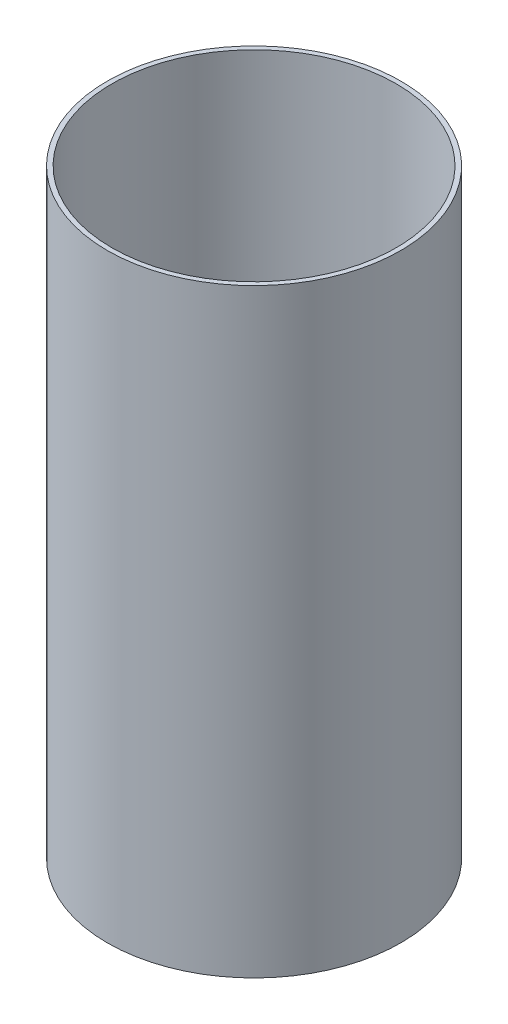
SolidWorks part; units mm, degrees
material "6061-T6 (SS)"
ref_plane "Front Plane" through (0, 0, 0) normal (0, 0, 1) x (1, 0, 0)
ref_plane "Top Plane" through (0, 0, 0) normal (0, 1, 0) x (1, 0, 0)
ref_plane "Right Plane" through (0, 0, 0) normal (1, 0, 0) x (0, 0, -1)
sketch "Sketch1" plane through (0, 0, 0) normal (0, 1, 0) x (1, 0, 0)
  circle A0 centre (0, 0) radius 104.14
  circle A1 centre (0, 0) radius 100.838
  dimension "D1" = 208.28
  dimension "D2" = 3.302
extrude "Boss-Extrude1" add sketch "Sketch1" along normal mid plane 425.45
